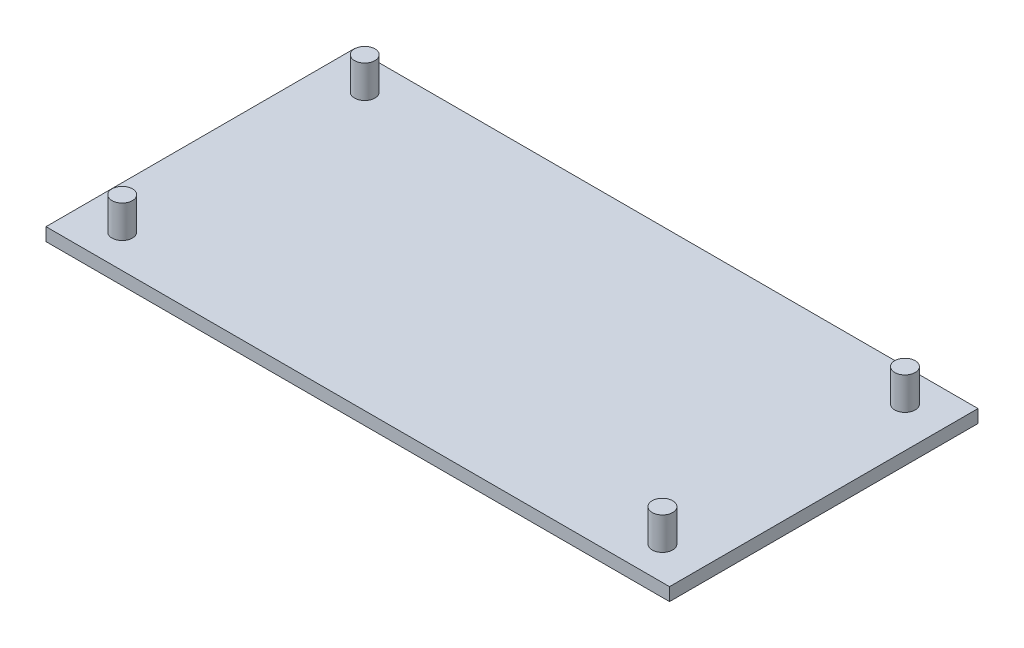
SolidWorks part; units mm, degrees
ref_plane "Front Plane" through (0, 0, 0) normal (0, 0, 1) x (1, 0, 0)
ref_plane "Top Plane" through (0, 0, 0) normal (0, 1, 0) x (1, 0, 0)
ref_plane "Right Plane" through (0, 0, 0) normal (1, 0, 0) x (0, 0, -1)
sketch "Sketch1" plane through (0, 0, 0) normal (0, 1, 0) x (1, 0, 0)
  line L0 (-50.1505, -23.6626) -> (-50.1505, 23.8464)
  line L1 (-50.1505, 23.8464) -> (45.8784, 23.8464)
  line L2 (45.8784, 23.8464) -> (45.8784, -23.6626)
  line L3 (45.8784, -23.6626) -> (-50.1505, -23.6626)
extrude "Boss-Extrude1" add sketch "Sketch1" along normal blind 2 contours L0 L1 L2 L3
sketch "Sketch2" plane through (0, 2, 0) normal (0, 1, 0) x (1, 0, 0)
  circle A8 centre (-43.5408, -18.5327) radius 1.575
  circle A9 centre (-43.5408, 18.8173) radius 1.575
  circle A10 centre (39.6592, -18.5327) radius 1.575
  circle A11 centre (39.6592, 18.8173) radius 1.575
extrude "Boss-Extrude2" add sketch "Sketch2" along normal blind 5
